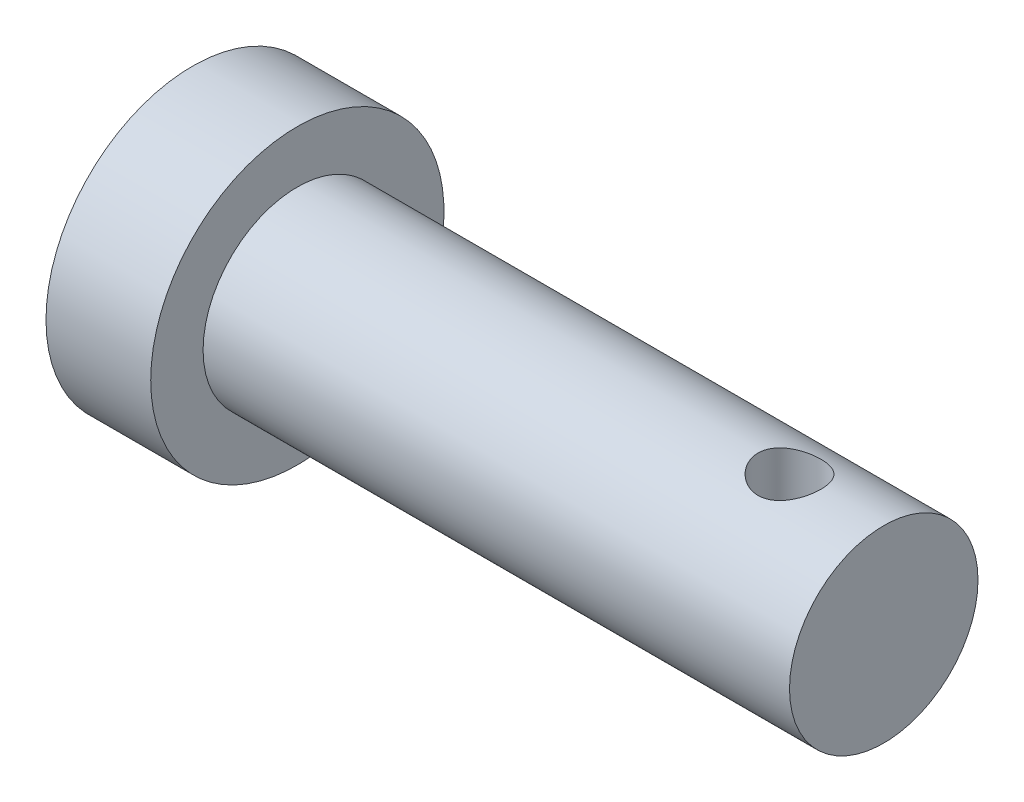
SolidWorks part; units mm, degrees
material "Brass"
ref_plane "Front Plane" through (0, 0, 0) normal (0, 0, 1) x (1, 0, 0)
ref_plane "Top Plane" through (0, 0, 0) normal (0, 1, 0) x (1, 0, 0)
ref_plane "Right Plane" through (0, 0, 0) normal (1, 0, 0) x (0, 0, -1)
sketch "Sketch1" plane through (0, 0, 0) normal (1, 0, 0) x (0, 0, -1)
  circle A0 centre (0, 0) radius 4.5
  dimension "D1" = 9
extrude "Boss-Extrude1" add sketch "Sketch1" along normal blind 33
sketch "Sketch2" plane through (0, 0, 0) normal (-1, 0, 0) x (0, 0, 1)
  circle A0 centre (0, 0) radius 7
  dimension "D1" = 14
extrude "Boss-Extrude2" add sketch "Sketch2" against normal blind 5
sketch "Sketch3" plane through (0, 0, 0) normal (0, 1, 0) x (1, 0, 0)
  line L0 (33, -4.5) -> (33, 4.5) construction
  circle A0 centre (28.5, 0) radius 1.5
  dimension "D1" = 3
  dimension "D2" = 4.5
extrude "Cut-Extrude1" cut sketch "Sketch3" against normal through all both and the other way through all
